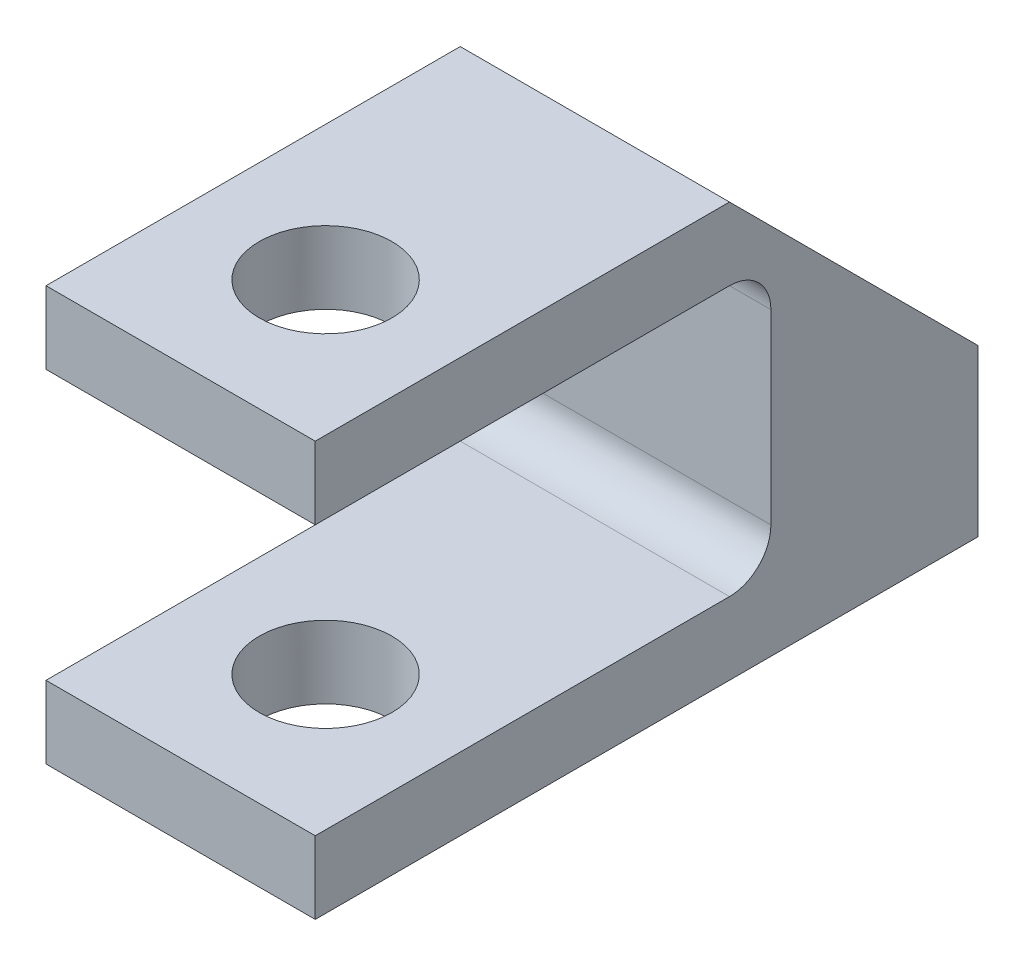
SolidWorks part; units mm, degrees
ref_plane "Front Plane" through (0, 0, 0) normal (0, 0, 1) x (1, 0, 0)
ref_plane "Top Plane" through (0, 0, 0) normal (0, 1, 0) x (1, 0, 0)
ref_plane "Right Plane" through (0, 0, 0) normal (1, 0, 0) x (0, 0, -1)
sketch "Sketch1" plane through (0, 0, 0) normal (1, 0, 0) x (0, 0, -1)
  line L1 (-8, -5) -> (8, -5)
  line L2 (-8, -5) -> (-8, 5)
  line L3 (-8, 5) -> (8, 5)
  line L4 (8, -5) -> (8, 5)
  line L5 (-8, -5) -> (8, 5) construction
  line L6 (-8, 5) -> (8, -5) construction
  point P0 (0, 0)
  dimension "D1" = 16
  dimension "D2" = 10
extrude "Boss-Extrude1" add sketch "Sketch1" against normal blind 6.5
sketch "Sketch2" plane through (0, 0, 0) normal (1, 0, 0) x (0, 0, -1)
  line L0 (8, -1) -> (2, 5)
  line L1 (8, -5) -> (8, 5) construction
  line L2 (8, 5) -> (-8, 5) construction
  line L3 (2, 5) -> (8, 5)
  line L4 (8, 5) -> (8, -1)
  dimension "D1" = 6
  dimension "D2" = 6
extrude "Cut-Extrude1" cut sketch "Sketch2" against normal through all
sketch "Sketch3" plane through (0, 0, 8) normal (0, 0, 1) x (1, 0, 0)
  line L0 (-3.25, 5) -> (-3.25, -5) construction
  line L1 (-6.5, 5) -> (0, 5) construction
  line L2 (-6.5, -5) -> (0, -5) construction
  line L4 (-10.25, -3.25) -> (3.75, -3.25)
  line L5 (-10.25, -3.25) -> (-10.25, 3.25)
  line L6 (-10.25, 3.25) -> (3.75, 3.25)
  line L7 (3.75, -3.25) -> (3.75, 3.25)
  line L8 (-10.25, -3.25) -> (3.75, 3.25) construction
  line L9 (-10.25, 3.25) -> (3.75, -3.25) construction
  point P6 (-3.25, 0)
  dimension "D1" = 14
  dimension "D2" = 6.5
extrude "Cut-Extrude2" cut sketch "Sketch3" against normal blind 11 contours L5 L4 L7 L6
sketch "Sketch4" plane through (0, 5, 0) normal (0, 1, 0) x (1, 0, 0)
  line L0 (-3.25, 2) -> (-3.25, -8) construction
  line L1 (-6.5, 2) -> (0, 2) construction
  line L2 (-6.5, -8) -> (0, -8) construction
  circle A1 centre (-3.25, -4.5) radius 1.6
  dimension "D1" = 3.2
  dimension "D2" = 3.5
extrude "Cut-Extrude3" cut sketch "Sketch4" against normal through all
fillet "Fillet1" radius 1 2 edges at (-3.25, -3.25, -3) (-3.25, 3.25, -3)
